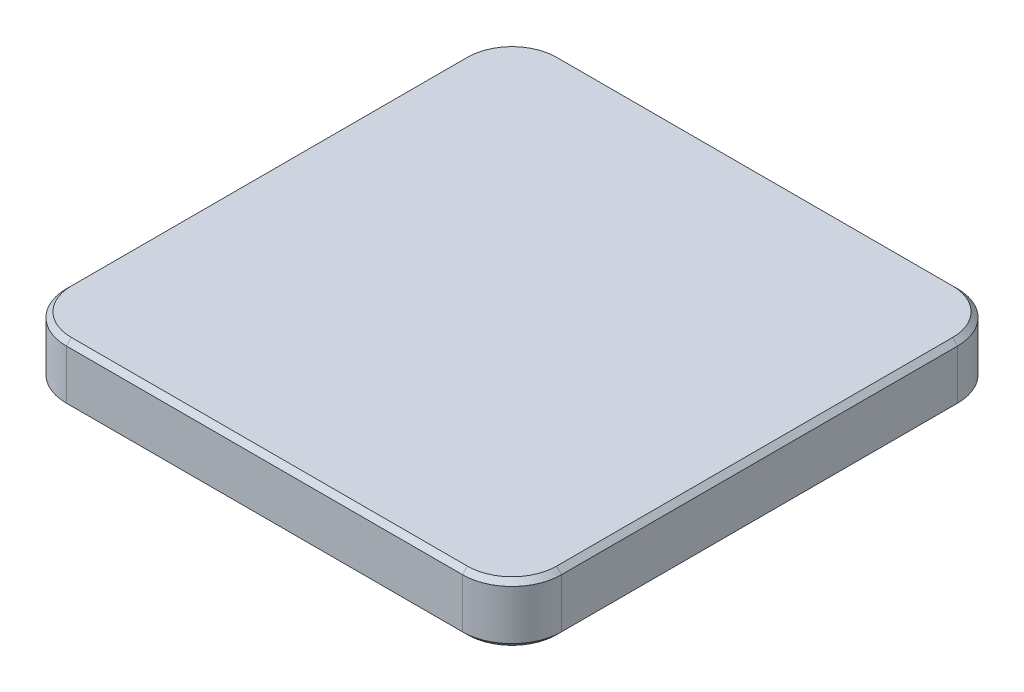
SolidWorks part; units mm, degrees
material "Tungsten"
ref_plane "Front Plane" through (0, 0, 0) normal (0, 0, 1) x (1, 0, 0)
ref_plane "Top Plane" through (0, 0, 0) normal (0, 1, 0) x (1, 0, 0)
ref_plane "Right Plane" through (0, 0, 0) normal (1, 0, 0) x (0, 0, -1)
sketch "Sketch2" plane through (0, 0, 0) normal (0, 1, 0) x (1, 0, 0)
  line L0 (-50, 40) -> (-50, -40)
  line L1 (-40, -50) -> (40, -50)
  line L2 (50, -40) -> (50, 40)
  line L3 (40, 50) -> (-40, 50)
  arc A0 (40, -50) -> (50, -40) centre (40, -40) ccw
  arc A1 (50, 40) -> (40, 50) centre (40, 40) ccw
  arc A2 (-50, 40) -> (-40, 50) centre (-40, 40) cw
  arc A3 (-50, -40) -> (-40, -50) centre (-40, -40) ccw
  point P13 (0, -50)
  point P14 (-50, 0)
  dimension "D1" = 10
  dimension "D2" = 100
extrude "Boss-Extrude1" add sketch "Sketch2" along normal blind 12
chamfer "Chamfer1" distance 1 angle 45 16 edges at (50, 0, 0) (47.0711, 0, -47.0711) (0, 0, -50) (-47.0711, 0, -47.0711) (-50, 0, 0) (-47.0711, 0, 47.0711) (0, 0, 50) (47.0711, 0, 47.0711) (0, 12, 50) (-47.0711, 12, 47.0711) (-50, 12, 0) (-47.0711, 12, -47.0711) (0, 12, -50) (47.0711, 12, -47.0711) (50, 12, 0) (47.0711, 12, 47.0711)
